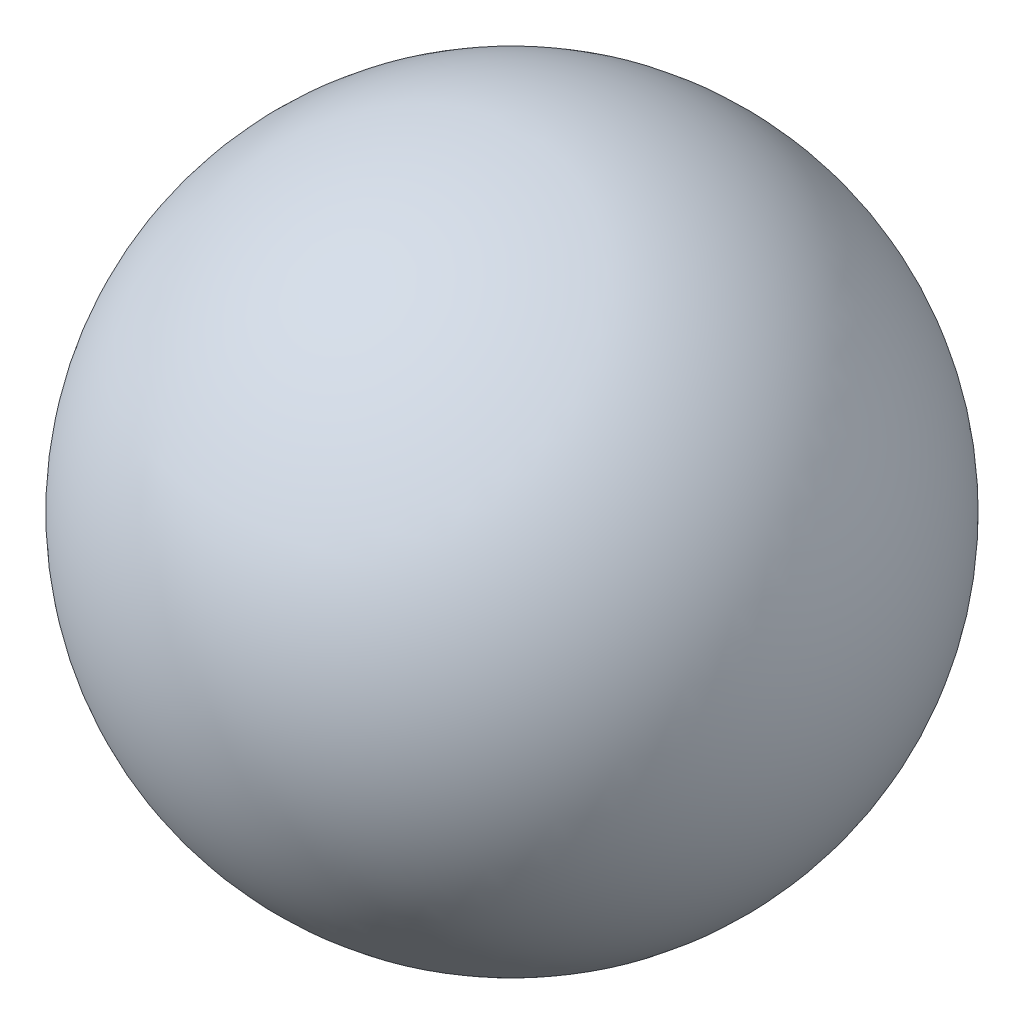
SolidWorks part; units mm, degrees
ref_plane "正面" through (0, 0, 0) normal (0, 0, 1) x (1, 0, 0)
ref_plane "平面" through (0, 0, 0) normal (0, 1, 0) x (1, 0, 0)
ref_plane "右側面" through (0, 0, 0) normal (1, 0, 0) x (0, 0, -1)
sketch "ｽｹｯﾁ1" plane through (0, 0, 0) normal (0, 0, 1) x (1, 0, 0)
  line L0 (0, 0) -> (0, 60)
  arc A0 (0, 60) -> (0, 0) centre (0, 30) cw
  dimension "D1" = 60
revolve "回転1" add sketch "ｽｹｯﾁ1" angle 360 about L0
